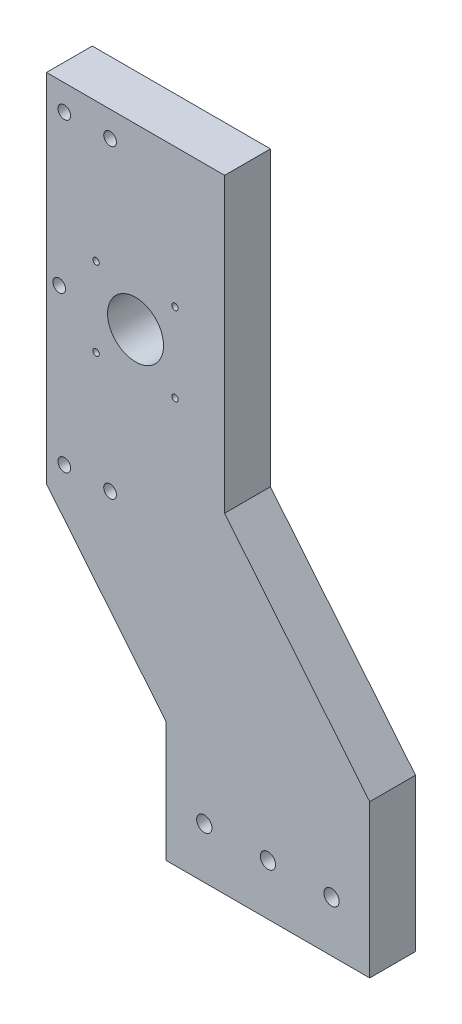
SolidWorks part; units mm, degrees
ref_plane "前视基准面" through (0, 0, 0) normal (0, 0, 1) x (1, 0, 0)
ref_plane "上视基准面" through (0, 0, 0) normal (0, 1, 0) x (1, 0, 0)
ref_plane "右视基准面" through (0, 0, 0) normal (1, 0, 0) x (0, 0, -1)
other "Configuration Table"
sketch "草图1" plane through (0, 0, 0) normal (0, 0, 1) x (1, 0, 0)
  line L0 (0, 0) -> (80, 0)
  line L2 (22.9864, 129.638) -> (22.9864, 244.638)
  line L5 (80, 0) -> (80, 60)
  line L6 (80, 60) -> (22.9864, 129.638)
  line L7 (0, 0) -> (0, 47.2143)
  line L8 (0, 47.2143) -> (-47.0136, 104.638)
  line L9 (-47.0136, 104.638) -> (-47.0136, 244.638)
  line L11 (-47.0136, 244.638) -> (22.9864, 244.638)
  dimension "D1" = 80
  dimension "D2" = 115
  dimension "D3" = 140
  dimension "D4" = 70
  dimension "D5" = 60
  dimension "D6" = 70
  dimension "D7" = 90
extrude "凸台-拉伸1" add sketch "草图1" along normal blind 18 contours L0 L5 L6 L2 L11 L9 L8 L7
sketch "草图2" plane through (0, 0, 18) normal (0, 0, 1) x (1, 0, 0)
  line L0 (-47.0136, 104.638) -> (-47.0136, 244.638) construction
  line L1 (-47.0136, 244.638) -> (22.9864, 244.638) construction
  line L2 (-47.0136, 174.638) -> (9.6331, 174.638) construction
  circle A0 centre (-40.0136, 234.638) radius 4
  circle A1 centre (-22.0136, 234.638) radius 4
  circle A2 centre (-22.0136, 114.638) radius 4
  circle A3 centre (-40.0136, 114.638) radius 4
  circle A4 centre (-42.0136, 174.638) radius 3
  dimension "D1" = 8
  dimension "D2" = 8
  dimension "D6" = 6
  dimension "D3" = 18
  dimension "D4" = 7
  dimension "D5" = 10
  dimension "D7" = 5
hole_wizard "M6 螺纹孔1" positions "草图4" profile "草图3" tap size "M6" standard "GB" end condition through all
sketch "草图4" plane through (0, 0, 18) normal (0, 0, 1) x (1, 0, 0)
  point P31 (-40.0136, 114.638)
  point P34 (-22.0136, 114.638)
  point P37 (-40.0136, 234.638)
  point P40 (-22.0136, 234.638)
  point P43 (-42.0136, 174.638)
sketch "草图3" plane through (-40.0136, 114.638, 18) normal (1, 0, 0) x (0, -1, 0)
  line L0 (0, 0) -> (0, 18)
  line L1 (0, 18) -> (2.5, 18)
  line L2 (2.5, 18) -> (2.5, 0)
  line L5 (2.5, 0) -> (0, 0)
  line L11 (0, -6.35) -> (0, 107.95) construction
  dimension "通孔螺纹孔钻头直径" = 5
  dimension "通孔螺纹孔钻头深度" = 18
cosmetic thread "孔螺蚊线1" parameters "D2"=6
cosmetic thread "孔螺蚊线2" parameters "D2"=6
cosmetic thread "孔螺蚊线7" parameters "D2"=6
cosmetic thread "孔螺蚊线8" parameters "D2"=6
cosmetic thread "孔螺蚊线9" parameters "D2"=6
sketch "草图6" plane through (0, 0, 18) normal (0, 0, 1) x (1, 0, 0)
  line L0 (0, 0) -> (80, 0) construction
  circle A0 centre (15, 20) radius 3
  circle A1 centre (65, 20) radius 3
  circle A2 centre (40, 20) radius 3
  dimension "D1" = 6
  dimension "D2" = 6
  dimension "D3" = 6
  dimension "D4" = 25
  dimension "D5" = 20
extrude "切除-拉伸1" cut sketch "草图6" against normal through all
sketch "草图7" plane through (0, 0, 18) normal (0, 0, 1) x (1, 0, 0)
  line L0 (-12.0136, 174.638) -> (12.8193, 174.638) construction
  line L1 (-12.0136, 174.638) -> (-12.0136, 171.616) construction
  circle A0 centre (-12.0136, 174.638) radius 11
  circle A1 centre (-12.0136, 174.638) radius 21.9203 construction
  circle A2 centre (-27.5136, 190.138) radius 1.25
  circle A3 centre (3.4864, 190.138) radius 1.25
  circle A4 centre (3.4864, 159.138) radius 1.25
  circle A5 centre (-27.5136, 159.138) radius 1.25
  dimension "D1" = 22
  dimension "D2" = 2.5
extrude "切除-拉伸2" cut sketch "草图7" against normal through all
